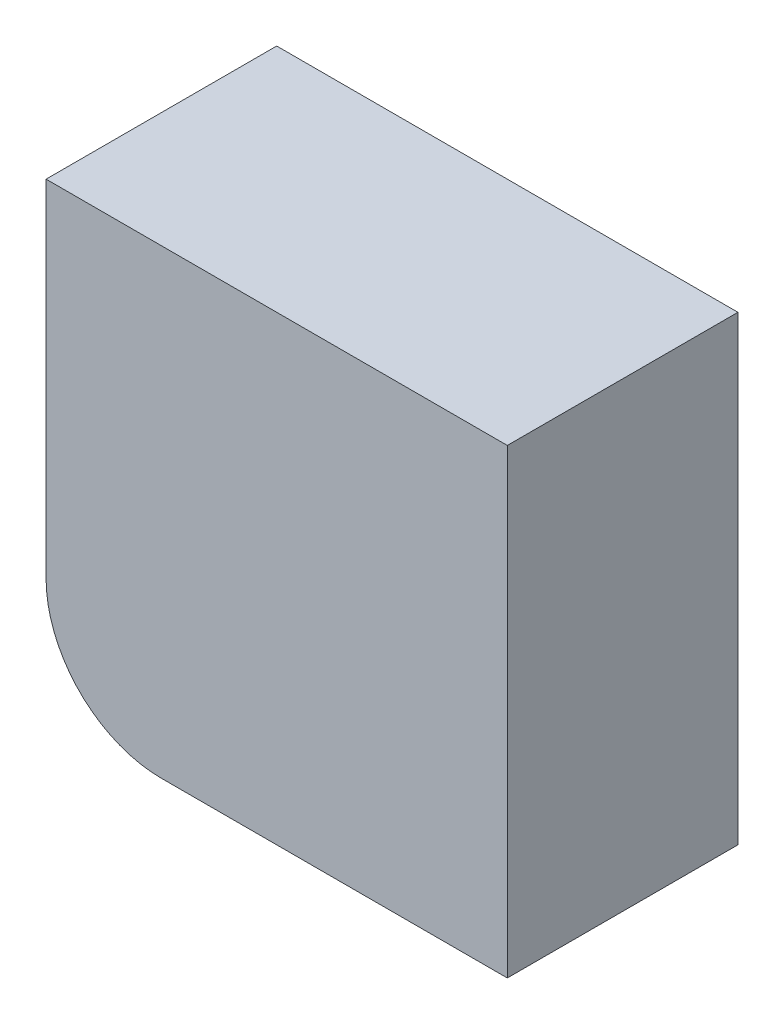
SolidWorks part; units mm, degrees
ref_plane "前视基准面" through (0, 0, 0) normal (0, 0, 1) x (1, 0, 0)
ref_plane "上视基准面" through (0, 0, 0) normal (0, 1, 0) x (1, 0, 0)
ref_plane "右视基准面" through (0, 0, 0) normal (1, 0, 0) x (0, 0, -1)
other "Configuration Table"
sketch "草图1" plane through (0, 0, 0) normal (0, 0, 1) x (1, 0, 0)
  line L1 (0, 0) -> (20, 0)
  line L2 (0, 0) -> (0, 20)
  line L3 (0, 20) -> (20, 20)
  line L4 (20, 0) -> (20, 20)
extrude "BaseBox" add sketch "草图1" along normal blind 10
fillet "Fillet" radius 5 1 edges at (0, 0, 5)
